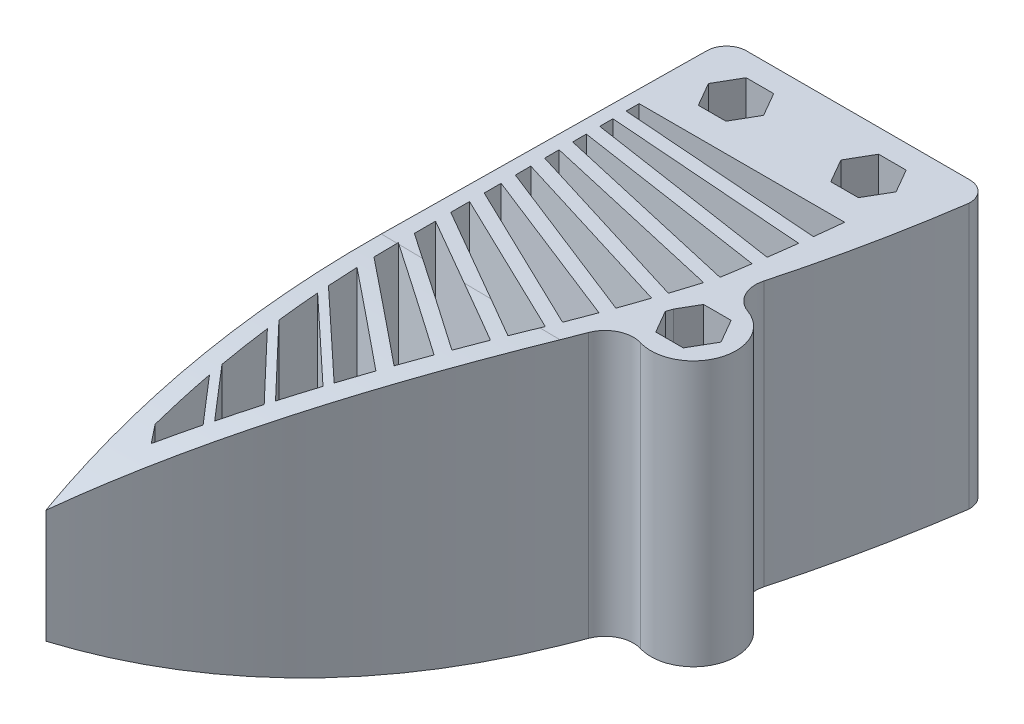
SolidWorks part; units mm, degrees
ref_plane "前视基准面" through (0, 0, 0) normal (0, 0, 1) x (1, 0, 0)
ref_plane "上视基准面" through (0, 0, 0) normal (0, 1, 0) x (1, 0, 0)
ref_plane "右视基准面" through (0, 0, 0) normal (1, 0, 0) x (0, 0, -1)
other "Configuration Table"
sketch "草图3" plane through (0, 0, 0) normal (0, 1, 0) x (1, 0, 0)
  line B0 (0, 120.3647) -> (0, 1)
  line B1 (36.724, 123.3647) -> (3, 123.3647)
  line B2 (6.4046, 13.5169) -> (1.8, 20.8875)
  line B3 (1.8, 20.8875) -> (1.8, 4.167)
  line B4 (10.1087, 21.7103) -> (1.8, 33.2384)
  line B5 (1.8, 23.1524) -> (7.0103, 14.8122)
  line B6 (1.8, 33.2384) -> (1.8, 23.1524)
  line B7 (13.3609, 29.5129) -> (1.8, 43.5031)
  line B8 (1.8, 35.2908) -> (10.6622, 22.9946)
  line B9 (1.8, 43.5031) -> (1.8, 35.2908)
  line B10 (16.224, 36.9613) -> (1.8, 52.2374)
  line B11 (1.8, 45.3869) -> (13.8664, 30.785)
  line B12 (1.8, 52.2374) -> (1.8, 45.3869)
  line B13 (18.7509, 44.0926) -> (1.8, 59.8201)
  line B14 (1.8, 53.9853) -> (16.6853, 38.2206)
  line B15 (1.8, 59.8201) -> (1.8, 53.9853)
  line B16 (20.8682, 50.5668) -> (1.8, 65.7724)
  line B17 (1.8, 61.457) -> (19.1715, 45.3393)
  line B18 (1.8, 65.7724) -> (1.8, 61.457)
  line B19 (22.9742, 57.5717) -> (1.8, 72.0074)
  line B20 (1.8, 68.3304) -> (21.5044, 52.6174)
  line B21 (1.8, 72.0074) -> (1.8, 68.3304)
  line B22 (24.8276, 64.329) -> (1.8, 77.6234)
  line B23 (1.8, 74.4279) -> (23.5489, 59.6005)
  line B24 (1.8, 77.6234) -> (1.8, 74.4279)
  line B25 (26.4619, 70.8851) -> (1.8, 82.7612)
  line B26 (1.8, 79.9327) -> (25.3458, 66.3392)
  line B27 (1.8, 82.7612) -> (1.8, 79.9327)
  line B28 (27.9039, 77.2845) -> (1.8, 87.5291)
  line B29 (1.8, 84.981) -> (26.9277, 72.8807)
  line B30 (1.8, 87.5291) -> (1.8, 84.981)
  line B31 (29.1751, 83.5691) -> (1.8, 92.0128)
  line B32 (1.8, 89.6776) -> (28.3208, 79.2693)
  line B33 (1.8, 92.0128) -> (1.8, 89.6776)
  line B34 (30.2921, 89.7796) -> (1.8, 96.2825)
  line B35 (1.8, 94.1058) -> (29.5459, 85.5477)
  line B36 (1.8, 96.2825) -> (1.8, 94.1058)
  line B37 (31.2672, 95.956) -> (1.8, 100.3973)
  line B38 (1.8, 98.334) -> (30.6188, 91.7565)
  line B39 (1.8, 100.3973) -> (1.8, 98.334)
  line B40 (32.1089, 102.1377) -> (1.8, 104.409)
  line B41 (1.8, 102.4199) -> (31.5513, 97.9358)
  line B42 (1.8, 104.409) -> (1.8, 102.4199)
  line B43 (32.8223, 108.3647) -> (1.8, 108.3647)
  line B44 (1.8, 106.4146) -> (32.3512, 104.1252)
  line B45 (1.8, 108.3647) -> (1.8, 106.4146)
  line B46 (1.8, 110.3647) -> (33.0229, 110.3647)
  line B47 (1.8, 113.3647) -> (1.8, 110.3647)
  line B48 (33.298, 113.3647) -> (1.8, 113.3647)
  arc B49 (1.8, 4.167) -> (6.4046, 13.5169) centre (-259.6074, 138.7114) ccw
  arc B50 (7.0103, 14.8122) -> (10.1087, 21.7103) centre (-259.6074, 138.7114) ccw
  arc B51 (10.6622, 22.9946) -> (13.3609, 29.5129) centre (-259.6074, 138.7114) ccw
  arc B52 (0, 1) -> (1.8457, 0.4664) centre (1, 1) ccw
  arc B53 (1.8457, 0.4664) -> (33.5274, 76.1799) centre (-207.4276, 132.52) ccw
  arc B54 (35.9053, 78.4473) -> (33.5274, 76.1799) centre (36.4486, 75.4969) ccw
  arc B55 (35.9053, 78.4473) -> (37.7492, 87.541) centre (35, 83.3647) ccw
  arc B56 (36.4422, 90.5556) -> (37.7492, 87.541) centre (39.3987, 90.0468) ccw
  arc B57 (36.4422, 90.5556) -> (39.7203, 120.2155) centre (-207.4276, 132.52) ccw
  arc B58 (39.7203, 120.2155) -> (36.724, 123.3647) centre (36.724, 120.3647) ccw
  arc B59 (3, 123.3647) -> (0, 120.3647) centre (3, 120.3647) ccw
  arc B60 (13.8664, 30.785) -> (16.224, 36.9613) centre (-259.6074, 138.7114) ccw
  arc B61 (16.6853, 38.2206) -> (18.7509, 44.0926) centre (-259.6074, 138.7114) ccw
  arc B62 (19.1715, 45.3393) -> (20.8682, 50.5668) centre (-259.6074, 138.7114) ccw
  arc B63 (21.5044, 52.6174) -> (22.9742, 57.5717) centre (-259.6074, 138.7114) ccw
  arc B64 (23.5489, 59.6005) -> (24.8276, 64.329) centre (-259.6074, 138.7114) ccw
  arc B65 (25.3458, 66.3392) -> (26.4619, 70.8851) centre (-259.6074, 138.7114) ccw
  arc B66 (26.9277, 72.8807) -> (27.9039, 77.2845) centre (-259.6074, 138.7114) ccw
  arc B67 (28.3208, 79.2693) -> (29.1751, 83.5691) centre (-259.6074, 138.7114) ccw
  circle B68 centre (35, 83.3647) radius 2
  arc B69 (29.5459, 85.5477) -> (30.2921, 89.7796) centre (-259.6074, 138.7114) ccw
  arc B70 (30.6188, 91.7565) -> (31.2672, 95.956) centre (-259.6074, 138.7114) ccw
  arc B71 (31.5513, 97.9358) -> (32.1089, 102.1377) centre (-259.6074, 138.7114) ccw
  arc B72 (32.3512, 104.1252) -> (32.8223, 108.3647) centre (-259.6074, 138.7114) ccw
  arc B73 (33.0229, 110.3647) -> (33.298, 113.3647) centre (-259.6074, 138.7114) ccw
  circle B74 centre (35, 118.3647) radius 2
  circle B75 centre (5, 118.3647) radius 2
sketch_block_instance "umi-1"
sketch_block "umi"
extrude "凸台-拉伸2" add sketch "草图3" along normal blind 40
scale "缩放比例2" scale about centroid uniform scaling yes scale factor 0.7
sketch "草图7" plane through (0, 34, 0) normal (0, 1, 0) x (1, 0, 0)
  line L1 (3.2917, 19.3564) -> (3.2917, 29.3564)
  line L2 (3.2917, 29.3564) -> (4.2917, 29.3564)
  line L3 (4.2917, 29.3564) -> (5.2917, 108.3072)
  line L4 (5.2917, 108.3072) -> (5.2917, 24.752) construction
  line L5 (5.2917, 108.3072) -> (5.2917, 24.752)
  arc A0 (6.5837, 24.3784) -> (28.7609, 77.3779) centre (-139.9076, 116.816) ccw construction
  arc A1 (3.2917, 19.3564) -> (6.5837, 24.3784) centre (-139.9076, 116.816) ccw
  arc A4 (5.2917, 24.752) -> (6.5837, 24.3784) centre (5.9917, 24.752) ccw construction
  arc A5 (5.2917, 24.752) -> (6.5837, 24.3784) centre (5.9917, 24.752) ccw
  dimension "D1" = 2
  dimension "D2" = 1
  dimension "D3" = 10
extrude "凸台-拉伸3" add sketch "草图7" against normal up to surface (28 mm away) up to face at (17.3284, 6, -98.8239)
sketch "草图6" plane through (0, 34, 0) normal (0, 1, 0) x (1, 0, 0)
  circle A0 centre (8.7917, 106.9072) radius 1.5
  circle A1 centre (29.7917, 106.9072) radius 1.5
  circle A2 centre (29.7917, 82.4072) radius 1.5
  dimension "D1" = 3
  dimension "D2" = 3
  dimension "D3" = 3
extrude "切除-拉伸4" cut sketch "草图6" against normal blind 30
sketch "草图9" plane through (0, 34, 0) normal (0, 1, 0) x (1, 0, 0)
  circle A0 centre (29.7917, 106.9072) radius 1.5 construction
  circle A1 centre (8.7917, 106.9072) radius 1.5 construction
  circle A2 centre (29.7917, 106.9072) radius 1.5
  circle A3 centre (8.7917, 106.9072) radius 1.5
extrude "凸台-拉伸5" add sketch "草图9" against normal up to surface (28 mm away) up to face at (8.7917, 6, -105.4072)
sketch "草图17" plane through (0, 34, 0) normal (0, 1, 0) x (1, 0, 0)
  line L3 (28.6003, 103.4072) -> (6.5517, 103.4072)
  line L4 (6.5517, 101.3072) -> (28.4078, 101.3072)
  line L5 (6.5517, 103.4072) -> (6.5517, 101.3072)
  line L6 (28.6003, 103.4072) -> (6.5517, 103.4072)
  line L7 (6.5517, 101.3072) -> (28.4078, 101.3072)
  line L8 (6.5517, 103.4072) -> (6.5517, 101.3072)
  arc A1 (28.4078, 101.3072) -> (28.6003, 103.4072) centre (-176.4334, 121.1499) ccw
  arc A2 (28.4078, 101.3072) -> (28.6003, 103.4072) centre (-176.4334, 121.1499) ccw
  dimension "D1" = 0
extrude "凸台-拉伸6" add sketch "草图17" against normal up to surface (28 mm away) up to face at (29.7917, 6, -80.9072)
sketch "草图12" plane through (0, 34, 0) normal (0, 1, 0) x (1, 0, 0)
  line L0 (30.9985, 110.4072) -> (7.3917, 110.4072) construction
  circle A0 centre (11.2917, 105.4072) radius 1.5
  circle A1 centre (25.2917, 105.4072) radius 1.5
  dimension "D1" = 3
  dimension "D2" = 5
  dimension "D3" = 6
  dimension "D4" = 3
  dimension "D6" = 14
extrude "切除-拉伸6" cut sketch "草图12" against normal blind 37
sketch "草图18" plane through (0, 34, 0) normal (0, 1, 0) x (1, 0, 0)
  line L0 (30.9985, 110.4072) -> (7.3917, 110.4072) construction
  line L1 (12.7495, 102.8822) -> (14.2073, 105.4072)
  line L2 (14.2073, 105.4072) -> (12.7495, 107.9322)
  line L3 (12.7495, 107.9322) -> (9.8339, 107.9322)
  line L4 (9.8339, 107.9322) -> (8.3761, 105.4072)
  line L5 (8.3761, 105.4072) -> (9.8339, 102.8822)
  line L6 (9.8339, 102.8822) -> (12.7495, 102.8822)
  line L7 (26.7495, 102.8822) -> (28.2073, 105.4072)
  line L8 (28.2073, 105.4072) -> (26.7495, 107.9322)
  line L9 (26.7495, 107.9322) -> (23.8339, 107.9322)
  line L10 (23.8339, 107.9322) -> (22.3761, 105.4072)
  line L11 (22.3761, 105.4072) -> (23.8339, 102.8822)
  line L12 (23.8339, 102.8822) -> (26.7495, 102.8822)
  circle A0 centre (11.2917, 105.4072) radius 2.525 construction
  circle A1 centre (25.2917, 105.4072) radius 2.525 construction
  dimension "D1" = 5.05
  dimension "D2" = 5.05
extrude "切除-拉伸8" cut sketch "草图18" against normal blind 30
sketch "草图21" plane through (0, 34, 0) normal (0, 1, 0) x (1, 0, 0)
  line L0 (4.4184, 39.3564) -> (4.4184, 19.3564) construction
  line L1 (5.2917, 108.3072) -> (4.2917, 29.3564) construction
  line L2 (0.5321, 19.3564) -> (4.4184, 19.3564)
  line L3 (4.4184, 19.3564) -> (45.4367, 19.3564)
  line L4 (33.096, 108.2028) -> (45.4367, 108.2028)
  line L5 (45.4367, 108.2028) -> (45.4367, 19.3564)
  line L6 (0.5321, 19.3564) -> (4.4184, 39.3564)
  arc A0 (4.4184, 39.3564) -> (33.096, 108.2028) centre (-115.3633, 129.6467) ccw
  dimension "D1" = 300
  dimension "D2" = 20
extrude "切除-拉伸10" cut sketch "草图21" against normal blind 35
sketch "草图22" plane through (0, 34, 0) normal (0, 1, 0) x (1, 0, 0)
  line L10 (4.4184, 39.3564) -> (4.4617, 42.7793)
  line L11 (5.2917, 108.3072) -> (4.4184, 39.3564) construction
  line L12 (31.1165, 108.4887) -> (33.096, 108.2028)
  arc A0 (4.4184, 39.3564) -> (33.096, 108.2028) centre (-115.3633, 129.6467) ccw construction
  arc A1 (4.4184, 39.3564) -> (33.096, 108.2028) centre (-115.3633, 129.6467) ccw
  arc A2 (4.4617, 42.7793) -> (31.1165, 108.4887) centre (-115.3633, 129.6467) ccw
  arc A3 (2.8213, 40.5603) -> (31.1165, 108.4887) centre (-115.3633, 129.6467) ccw construction
  dimension "D1" = 2
extrude "凸台-拉伸7" add sketch "草图22" against normal up to surface (28 mm away) up to face at (11.2917, 6, -105.4072)
sketch "草图23" plane through (0, 34, 0) normal (0, 1, 0) x (1, 0, 0)
  line L0 (6.5517, 47.3189) -> (6.5517, 45.7377) construction
  circle A0 centre (6.5517, 46.5283) radius 1
  dimension "D1" = 2
extrude "凸台-拉伸8" add sketch "草图23" against normal up to surface (28 mm away) up to face at (16.2256, 6, -88.1008)
sketch "草图13" plane through (3.9198, 0, 0.004) normal (-0.9999, 0, -0.0127) x (-0.0127, 0, 0.9999)
  line L0 (-108.3199, 20) -> (-39.3636, 20) construction
  line L1 (-108.3199, 34) -> (-108.3199, 6) construction
  line L3 (-108.3199, 34) -> (-39.3636, 34) construction
  line L4 (-74.3636, 34) -> (-39.3636, 34)
  line L5 (-39.3636, 34) -> (-39.3636, 26)
  line L6 (-39.3636, 6) -> (-39.3636, 14)
  line L7 (-74.3636, 6) -> (-39.3636, 6)
  line L8 (-54.7751, 34) -> (-88.5436, 34) construction
  line L10 (-39.3636, 34) -> (-39.3636, 6) construction
  line L11 (-108.3199, 34) -> (-39.3636, 34) construction
  spline S0 degree 2 poles (-74.3636, 34) (-53.2583, 34) (-39.3636, 26) knots 0.085144 0.085144 0.085144 1 1 1
  spline S1 degree 2 poles (-74.3636, 6) (-53.2583, 6) (-39.3636, 14) knots 0.085144 0.085144 0.085144 1 1 1
  dimension "D2" = 35
  dimension "D1" = 6
extrude "切除-拉伸7" cut sketch "草图13" against normal blind 37
sketch "草图24" plane through (0, 34, 0) normal (0, 1, 0) x (1, 0, 0)
  line L0 (23.8339, 102.8822) -> (26.7495, 102.8822) construction
  line L1 (31.2495, 84.9322) -> (28.3339, 84.9322)
  line L2 (28.3339, 84.9322) -> (26.8761, 82.4072)
  line L3 (26.8761, 82.4072) -> (28.3339, 79.8822)
  line L4 (28.3339, 79.8822) -> (31.2495, 79.8822)
  line L5 (31.2495, 79.8822) -> (32.7073, 82.4072)
  line L6 (32.7073, 82.4072) -> (31.2495, 84.9322)
  circle A0 centre (29.7917, 82.4072) radius 4.5
  circle A1 centre (29.7917, 82.4072) radius 2.525 construction
  dimension "D2" = 9
  dimension "D1" = 5.05
extrude "凸台-拉伸9" add sketch "草图24" against normal up to surface (28 mm away) up to face at (16.2256, 6, -88.1008)
fillet "圆角1" radius 3 2 edges at (28.348, 20, -86.6693) (26.1161, 20, -79.8112)
